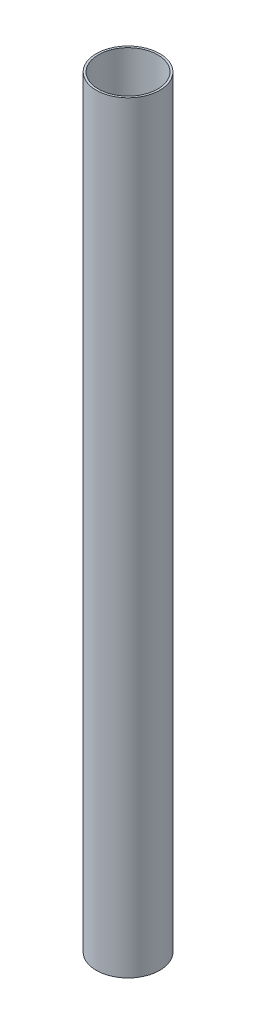
SolidWorks part; units mm, degrees
material "6061-T6 (SS)"
ref_plane "Front Plane" through (0, 0, 0) normal (0, 0, 1) x (1, 0, 0)
ref_plane "Top Plane" through (0, 0, 0) normal (0, 1, 0) x (1, 0, 0)
ref_plane "Right Plane" through (0, 0, 0) normal (1, 0, 0) x (0, 0, -1)
sketch "Sketch1" plane through (0, 0, 0) normal (0, 1, 0) x (1, 0, 0)
  circle A0 centre (0, 0) radius 12.7
  circle A1 centre (0, 0) radius 11.8745
  dimension "D1" = 25.4
  dimension "D2" = 23.749
extrude "Boss-Extrude1" add sketch "Sketch1" along normal mid plane 304.8
